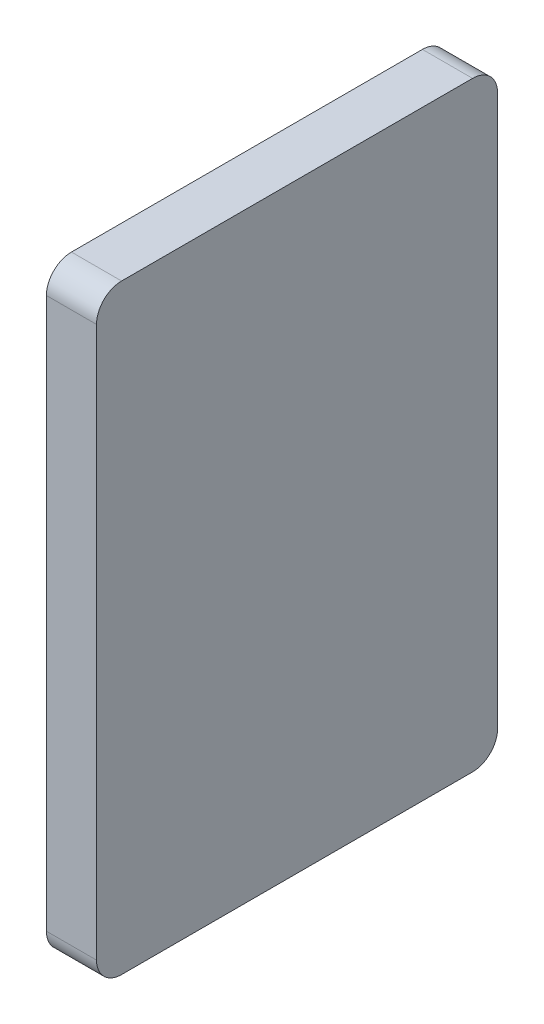
SolidWorks part; units mm, degrees
material "6061-T6 (SS)"
ref_plane "Front Plane" through (0, 0, 0) normal (0, 0, 1) x (1, 0, 0)
ref_plane "Top Plane" through (0, 0, 0) normal (0, 1, 0) x (1, 0, 0)
ref_plane "Right Plane" through (0, 0, 0) normal (1, 0, 0) x (0, 0, -1)
sketch "Sketch1" plane through (0, 0, 0) normal (1, 0, 0) x (0, 0, -1)
  line L0 (-1333.2378, 81.5316) -> (-1384.0378, 81.5316) construction
  line L1 (-1333.2378, 157.6046) -> (-1333.2378, 81.5316) construction
  line L2 (-1384.0378, 157.6046) -> (-1333.2378, 157.6046) construction
  line L3 (-1384.0378, 81.5316) -> (-1384.0378, 157.6046) construction
  line L4 (-1333.2378, 81.5316) -> (-1384.0378, 81.5316)
  line L5 (-1333.2378, 157.6046) -> (-1333.2378, 81.5316)
  line L6 (-1384.0378, 157.6046) -> (-1333.2378, 157.6046)
  line L7 (-1384.0378, 81.5316) -> (-1384.0378, 157.6046)
extrude "Boss-Extrude1" add sketch "Sketch1" along normal up to vertex (124.127 mm away) from vertex at 117.777
fillet "Fillet1" radius 3.175 4 edges at (120.952, 81.5316, 1333.2378) (120.952, 81.5316, 1384.0378) (120.952, 157.6046, 1333.2378) (120.952, 157.6046, 1384.0378)
